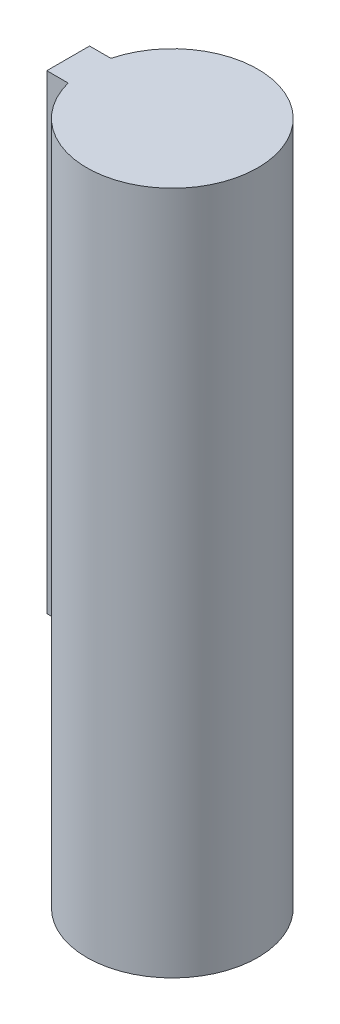
SolidWorks part; units mm, degrees
ref_plane "Front Plane" through (0, 0, 0) normal (0, 0, 1) x (1, 0, 0)
ref_plane "Top Plane" through (0, 0, 0) normal (0, 1, 0) x (1, 0, 0)
ref_plane "Right Plane" through (0, 0, 0) normal (1, 0, 0) x (0, 0, -1)
sketch "Sketch1" plane through (0, 0, 0) normal (0, 1, 0) x (1, 0, 0)
  circle A0 centre (0, 0) radius 20
  dimension "D1" = 40
extrude "Boss-Extrude1" add sketch "Sketch1" along normal mid plane 160
sketch "Sketch2" plane through (0, 80, 0) normal (0, 1, 0) x (1, 0, 0)
  line L0 (-20, 0) -> (0, 0) construction
  line L1 (-19.3649, 5) -> (-24.3649, 5)
  line L2 (-24.3649, 5) -> (-24.3649, -5)
  line L3 (-19.3649, -5) -> (-24.3649, -5)
  circle A0 centre (0, 0) radius 20 construction
  arc A1 (-19.3649, 5) -> (-19.3365, -5.1088) centre (0, 0) ccw
  point P10 (-24.3649, 0)
  circle M4 centre (0, 0) radius 20
  dimension "D1" = 5
  dimension "D2" = 5
extrude "Boss-Extrude2" add sketch "Sketch2" against normal blind 110 contours L3 A1 L1 L2 M4
